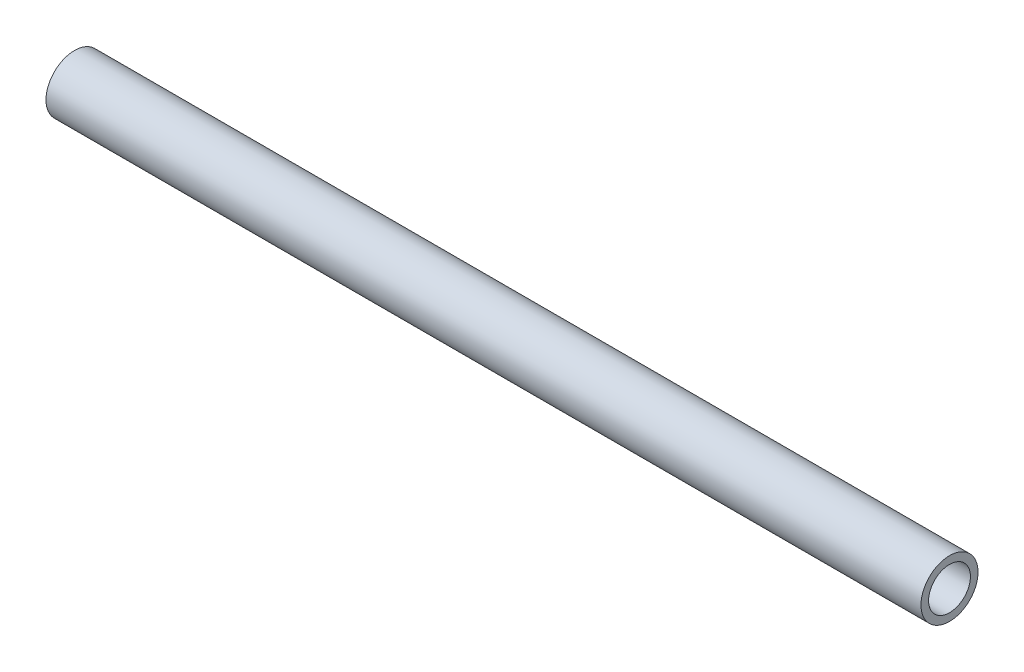
SolidWorks part; units mm, degrees
ref_plane "Front Plane" through (0, 0, 0) normal (0, 0, 1) x (1, 0, 0)
ref_plane "Top Plane" through (0, 0, 0) normal (0, 1, 0) x (1, 0, 0)
ref_plane "Right Plane" through (0, 0, 0) normal (1, 0, 0) x (0, 0, -1)
sketch "Axial profile (mm)" plane through (0, 0, 0) normal (0, 0, 1) x (1, 0, 0)
  line L0 (-110, 0) -> (75, 0) construction
  line L1 (49.7, 1.65) -> (118.7, 1.65)
  line L2 (118.7, 1.65) -> (118.7, 2.25)
  line L3 (118.7, 2.25) -> (49.7, 2.25)
  line L4 (49.7, 2.25) -> (49.7, 1.65)
revolve "Full revolution" add sketch "Axial profile (mm)" angle 360 about L0
